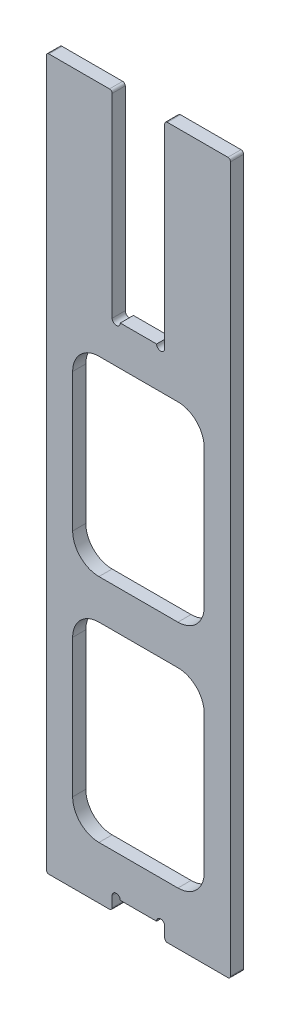
SolidWorks part; units mm, degrees
ref_plane "前视基准面" through (0, 0, 0) normal (0, 0, 1) x (1, 0, 0)
ref_plane "上视基准面" through (0, 0, 0) normal (0, 1, 0) x (1, 0, 0)
ref_plane "右视基准面" through (0, 0, 0) normal (1, 0, 0) x (0, 0, -1)
other "Configuration Table"
sketch "草图1" plane through (0, 0, 0) normal (0, 0, 1) x (1, 0, 0)
  line L1 (0, 0) -> (70, 0)
  line L2 (0, 0) -> (0, 190)
  line L3 (0, 190) -> (70, 190)
  line L4 (70, 0) -> (70, 190)
  line L5 (45, 0) -> (70, 0)
  line L6 (45, 0) -> (45, -5)
  line L7 (45, -5) -> (70, -5)
  line L8 (70, 0) -> (70, -5)
  line L9 (0, 0) -> (25, 0)
  line L10 (0, 0) -> (0, -5)
  line L11 (0, -5) -> (25, -5)
  line L12 (25, 0) -> (25, -5)
  line L13 (70, 190) -> (45, 190)
  line L14 (70, 190) -> (70, 195)
  line L15 (70, 195) -> (45, 195)
  line L16 (45, 190) -> (45, 195)
  line L17 (0, 190) -> (25, 190)
  line L18 (0, 190) -> (0, 195)
  line L19 (0, 195) -> (25, 195)
  line L20 (25, 190) -> (25, 195)
  dimension "D1" = 70
  dimension "D2" = 190
  dimension "D3" = 25
  dimension "D4" = 25
  dimension "D5" = 5
  dimension "D6" = 5
  dimension "D7" = 25
  dimension "D8" = 25
  dimension "D9" = 5
  dimension "D10" = 5
extrude "凸台-拉伸1" add sketch "草图1" along normal blind 5 contours L16 L3 L14 L15 | L1 L4 L3 L2 | L3 L20 L19 L18 | L8 L1 L6 L7 | L12 L1 L10 L11
sketch "草图2" plane through (0, 0, 5) normal (0, 0, 1) x (1, 0, 0)
  line L0 (25, 0) -> (45, 0) construction
  line L1 (45, 0) -> (45, -5) construction
  line L2 (25, 0) -> (25, -5) construction
  line L3 (25, 190) -> (45, 190) construction
  line L4 (25, 190) -> (25, 195) construction
  line L5 (45, 190) -> (45, 195) construction
  circle A0 centre (43.45, 0) radius 1.55
  circle A1 centre (26.55, 0) radius 1.55
  circle A2 centre (43.45, 190) radius 1.55
  circle A3 centre (26.55, 190) radius 1.55
  dimension "D4" = 3.1
extrude "切除-拉伸1" cut sketch "草图2" against normal blind 5
sketch "草图3" plane through (0, 0, 5) normal (0, 0, 1) x (1, 0, 0)
  line L0 (45, 190) -> (45, 195) construction
  line L1 (25, 195) -> (0, 195)
  line L2 (25, 195) -> (25, 265)
  line L3 (25, 265) -> (0, 265)
  line L4 (0, 195) -> (0, 265)
  line L5 (70, 195) -> (45, 195)
  line L6 (70, 195) -> (70, 265)
  line L7 (70, 265) -> (45, 265)
  line L8 (45, 195) -> (45, 265)
  point P12 (0, 195)
  dimension "D1" = 70
extrude "凸台-拉伸2" add sketch "草图3" against normal up to surface (5 mm away) up to face at (35, 95, 0)
sketch "草图4" plane through (0, 0, 5) normal (0, 0, 1) x (1, 0, 0)
  line L0 (35, 209.1485) -> (35, -17.7823) construction
  line L1 (70, -5) -> (70, 265) construction
  line L2 (0, -5) -> (0, 265) construction
  line L3 (-63.4445, 95) -> (174.1164, 95) construction
  line L4 (28.1, 0) -> (41.9, 0) construction
  line L5 (28.1, 190) -> (41.9, 190) construction
  line L6 (60, 102.5) -> (60, 175)
  line L7 (10, 87.5) -> (60, 87.5)
  line L8 (10, 87.5) -> (10, 15)
  line L9 (10, 15) -> (60, 15)
  line L10 (60, 87.5) -> (60, 15)
  line L11 (10, 175) -> (60, 175)
  line L12 (10, 102.5) -> (10, 175)
  line L13 (10, 102.5) -> (60, 102.5)
  dimension "D1" = 7.5
  dimension "D2" = 10
  dimension "D3" = 15
extrude "切除-拉伸2" cut sketch "草图4" against normal up to surface (5 mm away) up to face at (35, 112.5, 0)
fillet "圆角1" radius 10 8 edges at (60, 15, 2.5) (10, 15, 2.5) (10, 87.5, 2.5) (60, 87.5, 2.5) (60, 102.5, 2.5) (10, 102.5, 2.5) (10, 175, 2.5) (60, 175, 2.5)
fillet "圆角2" radius 1 8 edges at (0, 265, 2.5) (25, 265, 2.5) (45, 265, 2.5) (70, 265, 2.5) (70, -5, 2.5) (45, -5, 2.5) (25, -5, 2.5) (0, -5, 2.5)
